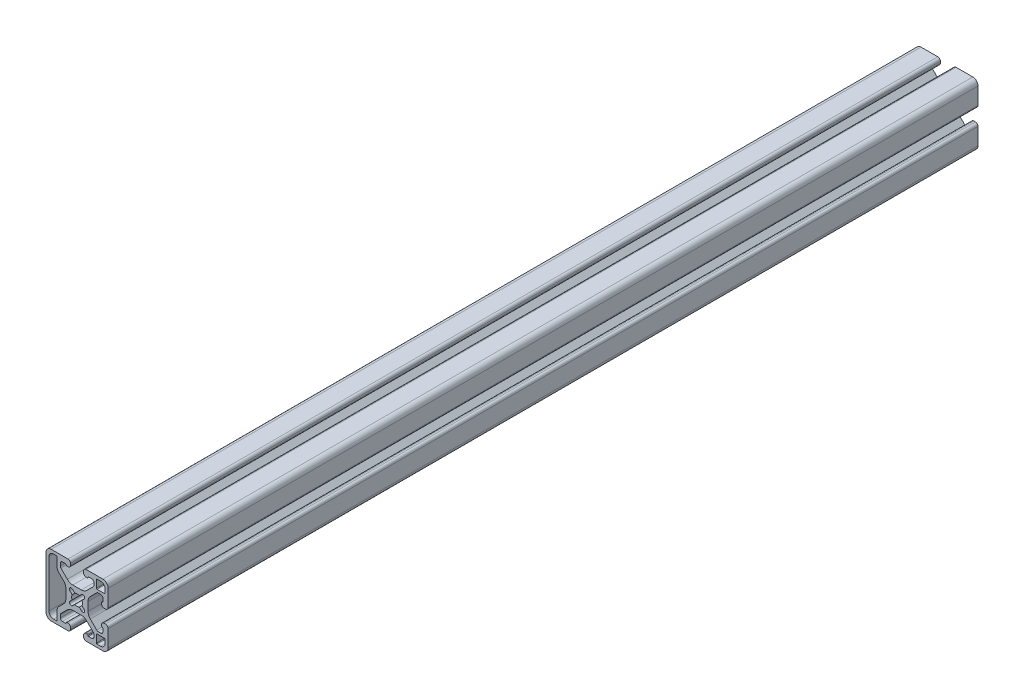
SolidWorks part; units mm, degrees
ref_plane "Front Plane" through (0, 0, 0) normal (0, 0, 1) x (1, 0, 0)
ref_plane "Top Plane" through (0, 0, 0) normal (0, 1, 0) x (1, 0, 0)
ref_plane "Right Plane" through (0, 0, 0) normal (1, 0, 0) x (0, 0, -1)
ref_plane "Plane1" through (0, 0, -533.4) normal (0, 0, -1) x (-1, 0, 0)
sketch "Sketch1" plane through (0, 0, -533.4) normal (0, 0, -1) x (-1, 0, 0)
  line L0 (17.2463, 14.4523) -> (17.2463, -14.4523)
  line L1 (14.4523, -17.2463) -> (12.5803, -17.2463)
  line L2 (12.1993, -16.8653) -> (12.1993, -11.3592)
  line L3 (11.2694, -9.1141) -> (8.2569, -6.1016)
  line L4 (6.8657, -2.743) -> (6.8657, 2.743)
  line L5 (8.2569, 6.1016) -> (11.2694, 9.1141)
  line L6 (12.1993, 11.3592) -> (12.1993, 16.8653)
  line L7 (12.5803, 17.2463) -> (14.4523, 17.2463)
  line L8 (3.0179, -1.4014) -> (4.3433, -2.7269)
  line L9 (2.7269, -4.3433) -> (1.4014, -3.0179)
  line L10 (-1.4014, -3.0179) -> (-2.7269, -4.3433)
  line L11 (-4.3433, -2.7269) -> (-3.0179, -1.4014)
  line L12 (-3.0179, 1.4014) -> (-4.3433, 2.7269)
  line L13 (-2.7269, 4.3433) -> (-1.4014, 3.0179)
  line L14 (1.4014, 3.0179) -> (2.7269, 4.3433)
  line L15 (4.3433, 2.7269) -> (3.0179, 1.4014)
  line L16 (-11.8618, 16.8656) -> (-11.8618, 12.2428)
  line L17 (-12.2428, 11.8618) -> (-16.8656, 11.8618)
  line L18 (-17.2466, 12.2428) -> (-17.2466, 14.4526)
  line L19 (-14.4526, 17.2466) -> (-12.2428, 17.2466)
  line L20 (-11.8618, -12.2428) -> (-11.8618, -16.8656)
  line L21 (-12.2428, -17.2466) -> (-14.4526, -17.2466)
  line L22 (-17.2466, -14.4526) -> (-17.2466, -12.2428)
  line L23 (-16.8656, -11.8618) -> (-12.2428, -11.8618)
  line L24 (19.05, -15.875) -> (19.05, 15.875)
  line L25 (15.875, 19.05) -> (5.5795, 19.05)
  line L26 (4.0057, 17.5302) -> (3.9737, 16.6158)
  line L27 (5.5476, 14.986) -> (6.2683, 14.986)
  line L28 (6.6491, 15.3537) -> (6.6527, 15.4565)
  line L29 (7.0335, 15.8242) -> (9.017, 15.8242)
  line L30 (10.287, 14.5542) -> (10.287, 12.9683)
  line L31 (9.915, 12.0703) -> (5.9669, 8.1222)
  line L32 (2.6083, 6.731) -> (-2.6083, 6.731)
  line L33 (-5.9669, 8.1222) -> (-9.915, 12.0703)
  line L34 (-10.287, 12.9683) -> (-10.287, 14.5542)
  line L35 (-9.017, 15.8242) -> (-7.0335, 15.8242)
  line L36 (-6.6527, 15.4565) -> (-6.6491, 15.3537)
  line L37 (-6.2683, 14.986) -> (-5.5476, 14.986)
  line L38 (-3.9737, 16.6158) -> (-4.0057, 17.5302)
  line L39 (-5.5795, 19.05) -> (-15.875, 19.05)
  line L40 (-19.05, 15.875) -> (-19.05, 5.5795)
  line L41 (-17.5302, 4.0057) -> (-16.6158, 3.9737)
  line L42 (-14.986, 5.5476) -> (-14.986, 6.2683)
  line L43 (-15.3537, 6.6491) -> (-15.4565, 6.6527)
  line L44 (-15.8242, 7.0335) -> (-15.8242, 9.017)
  line L45 (-14.5542, 10.287) -> (-12.9683, 10.287)
  line L46 (-12.0703, 9.915) -> (-8.1222, 5.9669)
  line L47 (-6.731, 2.6083) -> (-6.731, -2.6083)
  line L48 (-8.1222, -5.9669) -> (-12.0703, -9.915)
  line L49 (-12.9683, -10.287) -> (-14.5542, -10.287)
  line L50 (-15.8242, -9.017) -> (-15.8242, -7.0335)
  line L51 (-15.4565, -6.6527) -> (-15.3537, -6.6491)
  line L52 (-14.986, -6.2683) -> (-14.986, -5.5476)
  line L53 (-16.6158, -3.9737) -> (-17.5302, -4.0057)
  line L54 (-19.05, -5.5795) -> (-19.05, -15.875)
  line L55 (-15.875, -19.05) -> (-5.5795, -19.05)
  line L56 (-4.0057, -17.5302) -> (-3.9737, -16.6158)
  line L57 (-5.5476, -14.986) -> (-6.2683, -14.986)
  line L58 (-6.6491, -15.3537) -> (-6.6527, -15.4565)
  line L59 (-7.0335, -15.8242) -> (-9.017, -15.8242)
  line L60 (-10.287, -14.5542) -> (-10.287, -12.9683)
  line L61 (-9.915, -12.0703) -> (-5.9669, -8.1222)
  line L62 (-2.6083, -6.731) -> (2.6083, -6.731)
  line L63 (5.9669, -8.1222) -> (9.915, -12.0703)
  line L64 (10.287, -12.9683) -> (10.287, -14.5542)
  line L65 (9.017, -15.8242) -> (7.0335, -15.8242)
  line L66 (6.6527, -15.4565) -> (6.6491, -15.3537)
  line L67 (6.2683, -14.986) -> (5.5476, -14.986)
  line L68 (3.9737, -16.6158) -> (4.0057, -17.5302)
  line L69 (5.5795, -19.05) -> (15.875, -19.05)
  arc A0 (17.2463, -14.4523) -> (14.4523, -17.2463) centre (14.4523, -14.4523) cw
  arc A1 (12.5803, -17.2463) -> (12.1993, -16.8653) centre (12.5803, -16.8653) cw
  arc A2 (12.1993, -11.3592) -> (11.2694, -9.1141) centre (9.0243, -11.3592) ccw
  arc A3 (8.2569, -6.1016) -> (6.8657, -2.743) centre (11.6155, -2.743) cw
  arc A4 (6.8657, 2.743) -> (8.2569, 6.1016) centre (11.6155, 2.743) cw
  arc A5 (11.2694, 9.1141) -> (12.1993, 11.3592) centre (9.0243, 11.3592) ccw
  arc A6 (12.1993, 16.8653) -> (12.5803, 17.2463) centre (12.5803, 16.8653) cw
  arc A7 (14.4523, 17.2463) -> (17.2463, 14.4523) centre (14.4523, 14.4523) cw
  arc A8 (4.3433, -2.7269) -> (2.7269, -4.3433) centre (3.5351, -3.5351) cw
  arc A9 (1.4014, -3.0179) -> (-1.4014, -3.0179) centre (0, 0) cw
  arc A10 (-2.7269, -4.3433) -> (-4.3433, -2.7269) centre (-3.5351, -3.5351) cw
  arc A11 (-3.0179, -1.4014) -> (-3.0179, 1.4014) centre (0, 0) cw
  arc A12 (-4.3433, 2.7269) -> (-2.7269, 4.3433) centre (-3.5351, 3.5351) cw
  arc A13 (-1.4014, 3.0179) -> (1.4014, 3.0179) centre (0, 0) cw
  arc A14 (2.7269, 4.3433) -> (4.3433, 2.7269) centre (3.5351, 3.5351) cw
  arc A15 (3.0179, 1.4014) -> (3.0179, -1.4014) centre (0, 0) cw
  arc A16 (-11.8618, 12.2428) -> (-12.2428, 11.8618) centre (-12.2428, 12.2428) cw
  arc A17 (-16.8656, 11.8618) -> (-17.2466, 12.2428) centre (-16.8656, 12.2428) cw
  arc A18 (-17.2466, 14.4526) -> (-14.4526, 17.2466) centre (-14.4526, 14.4526) cw
  arc A19 (-12.2428, 17.2466) -> (-11.8618, 16.8656) centre (-12.2428, 16.8656) cw
  arc A20 (-12.2428, -11.8618) -> (-11.8618, -12.2428) centre (-12.2428, -12.2428) cw
  arc A21 (-11.8618, -16.8656) -> (-12.2428, -17.2466) centre (-12.2428, -16.8656) cw
  arc A22 (-14.4526, -17.2466) -> (-17.2466, -14.4526) centre (-14.4526, -14.4526) cw
  arc A23 (-17.2466, -12.2428) -> (-16.8656, -11.8618) centre (-16.8656, -12.2428) cw
  arc A24 (19.05, 15.875) -> (15.875, 19.05) centre (15.875, 15.875) ccw
  arc A25 (5.5795, 19.05) -> (4.0057, 17.5302) centre (5.5795, 17.4752) ccw
  arc A26 (3.9737, 16.6158) -> (5.5476, 14.986) centre (5.5476, 16.5608) ccw
  arc A27 (6.2683, 14.986) -> (6.6491, 15.3537) centre (6.2683, 15.367) ccw
  arc A28 (6.6527, 15.4565) -> (7.0335, 15.8242) centre (7.0335, 15.4432) cw
  arc A29 (9.017, 15.8242) -> (10.287, 14.5542) centre (9.017, 14.5542) cw
  arc A30 (10.287, 12.9683) -> (9.915, 12.0703) centre (9.017, 12.9683) cw
  arc A31 (5.9669, 8.1222) -> (2.6083, 6.731) centre (2.6083, 11.4808) cw
  arc A32 (-2.6083, 6.731) -> (-5.9669, 8.1222) centre (-2.6083, 11.4808) cw
  arc A33 (-9.915, 12.0703) -> (-10.287, 12.9683) centre (-9.017, 12.9683) cw
  arc A34 (-10.287, 14.5542) -> (-9.017, 15.8242) centre (-9.017, 14.5542) cw
  arc A35 (-7.0335, 15.8242) -> (-6.6527, 15.4565) centre (-7.0335, 15.4432) cw
  arc A36 (-6.6491, 15.3537) -> (-6.2683, 14.986) centre (-6.2683, 15.367) ccw
  arc A37 (-5.5476, 14.986) -> (-3.9737, 16.6158) centre (-5.5476, 16.5608) ccw
  arc A38 (-4.0057, 17.5302) -> (-5.5795, 19.05) centre (-5.5795, 17.4752) ccw
  arc A39 (-15.875, 19.05) -> (-19.05, 15.875) centre (-15.875, 15.875) ccw
  arc A40 (-19.05, 5.5795) -> (-17.5302, 4.0057) centre (-17.4752, 5.5795) ccw
  arc A41 (-16.6158, 3.9737) -> (-14.986, 5.5476) centre (-16.5608, 5.5476) ccw
  arc A42 (-14.986, 6.2683) -> (-15.3537, 6.6491) centre (-15.367, 6.2683) ccw
  arc A43 (-15.4565, 6.6527) -> (-15.8242, 7.0335) centre (-15.4432, 7.0335) cw
  arc A44 (-15.8242, 9.017) -> (-14.5542, 10.287) centre (-14.5542, 9.017) cw
  arc A45 (-12.9683, 10.287) -> (-12.0703, 9.915) centre (-12.9683, 9.017) cw
  arc A46 (-8.1222, 5.9669) -> (-6.731, 2.6083) centre (-11.4808, 2.6083) cw
  arc A47 (-6.731, -2.6083) -> (-8.1222, -5.9669) centre (-11.4808, -2.6083) cw
  arc A48 (-12.0703, -9.915) -> (-12.9683, -10.287) centre (-12.9683, -9.017) cw
  arc A49 (-14.5542, -10.287) -> (-15.8242, -9.017) centre (-14.5542, -9.017) cw
  arc A50 (-15.8242, -7.0335) -> (-15.4565, -6.6527) centre (-15.4432, -7.0335) cw
  arc A51 (-15.3537, -6.6491) -> (-14.986, -6.2683) centre (-15.367, -6.2683) ccw
  arc A52 (-14.986, -5.5476) -> (-16.6158, -3.9737) centre (-16.5608, -5.5476) ccw
  arc A53 (-17.5302, -4.0057) -> (-19.05, -5.5795) centre (-17.4752, -5.5795) ccw
  arc A54 (-19.05, -15.875) -> (-15.875, -19.05) centre (-15.875, -15.875) ccw
  arc A55 (-5.5795, -19.05) -> (-4.0057, -17.5302) centre (-5.5795, -17.4752) ccw
  arc A56 (-3.9737, -16.6158) -> (-5.5476, -14.986) centre (-5.5476, -16.5608) ccw
  arc A57 (-6.2683, -14.986) -> (-6.6491, -15.3537) centre (-6.2683, -15.367) ccw
  arc A58 (-6.6527, -15.4565) -> (-7.0335, -15.8242) centre (-7.0335, -15.4432) cw
  arc A59 (-9.017, -15.8242) -> (-10.287, -14.5542) centre (-9.017, -14.5542) cw
  arc A60 (-10.287, -12.9683) -> (-9.915, -12.0703) centre (-9.017, -12.9683) cw
  arc A61 (-5.9669, -8.1222) -> (-2.6083, -6.731) centre (-2.6083, -11.4808) cw
  arc A62 (2.6083, -6.731) -> (5.9669, -8.1222) centre (2.6083, -11.4808) cw
  arc A63 (9.915, -12.0703) -> (10.287, -12.9683) centre (9.017, -12.9683) cw
  arc A64 (10.287, -14.5542) -> (9.017, -15.8242) centre (9.017, -14.5542) cw
  arc A65 (7.0335, -15.8242) -> (6.6527, -15.4565) centre (7.0335, -15.4432) cw
  arc A66 (6.6491, -15.3537) -> (6.2683, -14.986) centre (6.2683, -15.367) ccw
  arc A67 (5.5476, -14.986) -> (3.9737, -16.6158) centre (5.5476, -16.5608) ccw
  arc A68 (4.0057, -17.5302) -> (5.5795, -19.05) centre (5.5795, -17.4752) ccw
  arc A69 (15.875, -19.05) -> (19.05, -15.875) centre (15.875, -15.875) ccw
extrude "Boss-Extrude1" add sketch "Sketch1" against normal blind 533.4
